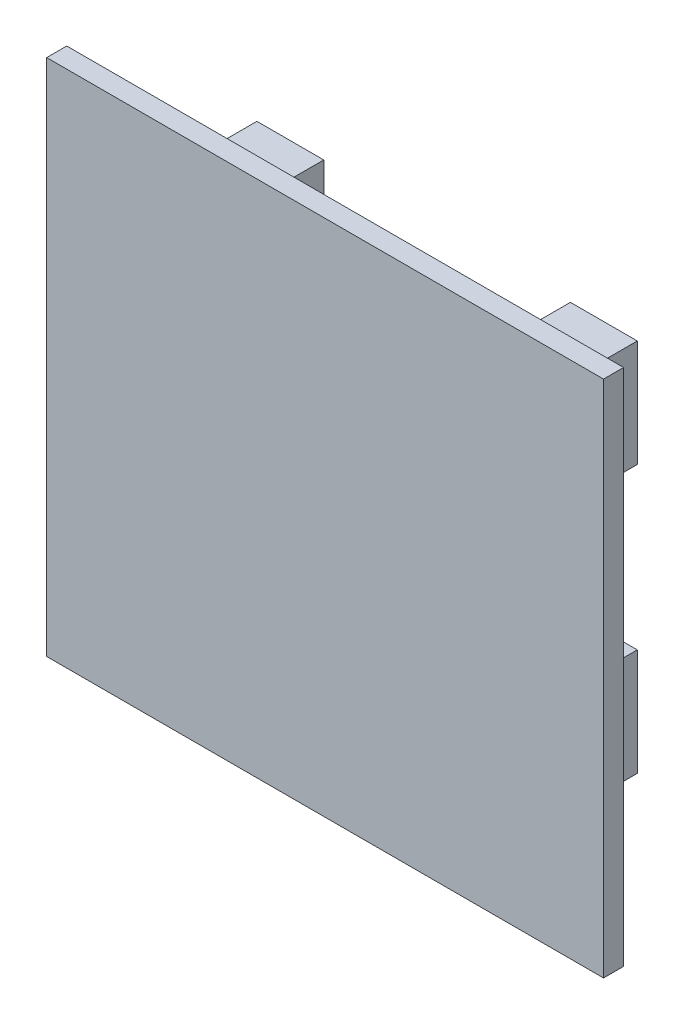
SolidWorks part; units mm, degrees
ref_plane "Front Plane" through (0, 0, 0) normal (0, 0, 1) x (1, 0, 0)
ref_plane "Top Plane" through (0, 0, 0) normal (0, 1, 0) x (1, 0, 0)
ref_plane "Right Plane" through (0, 0, 0) normal (1, 0, 0) x (0, 0, -1)
sketch "Sketch1" plane through (0, 0, 0) normal (0, 0, 1) x (1, 0, 0)
  line L1 (-208.15, 193.891) -> (208.15, 193.891)
  line L2 (-208.15, 193.891) -> (-208.15, -193.891)
  line L3 (-208.15, -193.891) -> (208.15, -193.891)
  line L4 (208.15, 193.891) -> (208.15, -193.891)
  line L5 (-208.15, 193.891) -> (208.15, -193.891) construction
  line L6 (-208.15, -193.891) -> (208.15, 193.891) construction
  point P0 (0, 0)
  dimension "D1" = 416.3
  dimension "D2" = 387.782
extrude "Boss-Extrude1" add sketch "Sketch1" along normal mid plane 15
sketch "Sketch3" plane through (0, 0, -7.5) normal (0, 0, -1) x (-1, 0, 0)
  line L0 (-300.2235, 0) -> (-180.2235, 0) construction
  line L1 (0, 239.7758) -> (0, -251.8653) construction
  line L3 (92.2, 140) -> (142.2, 140)
  line L4 (92.2, 140) -> (92.2, 60)
  line L5 (92.2, 60) -> (142.2, 60)
  line L6 (142.2, 140) -> (142.2, 60)
  line L7 (92.2, 140) -> (142.2, 60) construction
  line L8 (92.2, 60) -> (142.2, 140) construction
  line L9 (92.2, -60) -> (142.2, -140) construction
  line L10 (92.2, -140) -> (142.2, -60) construction
  line L11 (142.2, -140) -> (142.2, -60)
  line L12 (92.2, -60) -> (142.2, -60)
  line L13 (92.2, -140) -> (92.2, -60)
  line L14 (92.2, -140) -> (142.2, -140)
  line L15 (-92.2, -140) -> (-142.2, -60) construction
  line L16 (-92.2, -60) -> (-142.2, -140) construction
  line L17 (-92.2, 60) -> (-142.2, 140) construction
  line L18 (-92.2, 140) -> (-142.2, 60) construction
  line L19 (-92.2, -140) -> (-142.2, -140)
  line L20 (-92.2, -140) -> (-92.2, -60)
  line L21 (-92.2, -60) -> (-142.2, -60)
  line L22 (-142.2, -140) -> (-142.2, -60)
  line L23 (-142.2, 140) -> (-142.2, 60)
  line L24 (-92.2, 60) -> (-142.2, 60)
  line L25 (-92.2, 140) -> (-92.2, 60)
  line L26 (-92.2, 140) -> (-142.2, 140)
  line L27 (315.1093, 0) -> (-348.5322, 0) construction
  line L28 (-25, 40) -> (25, 40)
  line L29 (-25, 40) -> (-25, -40)
  line L30 (-25, -40) -> (25, -40)
  line L31 (25, 40) -> (25, -40)
  line L32 (-25, 40) -> (25, -40) construction
  line L33 (-25, -40) -> (25, 40) construction
  point P5 (117.2, 100)
  point P16 (117.2, -100)
  point P25 (-117.2, -100)
  point P26 (-117.2, 100)
  point P27 (0, 0)
  dimension "D1" = 80
  dimension "D2" = 100
  dimension "D3" = 50
  dimension "D4" = 100
  dimension "D5" = 80
  dimension "D6" = 50
extrude "Boss-Extrude2" add sketch "Sketch3" along normal blind 76.2
sketch "Sketch5" plane through (-142.2, 0, 0) normal (-1, 0, 0) x (0, 0, 1)
  line L0 (55.6499, 100) -> (-146.8499, 100) construction
  line L1 (-45.6, 187.9772) -> (-45.6, -258.3282) construction
  line L2 (-119.6484, -100) -> (118.1125, -100) construction
  line L7 (-83.7, 60) -> (-7.5, 60) construction
  line L8 (-83.7, -140) -> (-7.5, -140) construction
  line L9 (-83.7, 60) -> (-83.7, 140) construction
  circle A0 centre (-45.6, 100) radius 15.5
  circle A1 centre (-45.6, -100) radius 15.5
  dimension "D1" = 40
  dimension "D2" = 40
  dimension "D3" = 38.1
  dimension "D4" = 200
extrude "Cut-Extrude1" cut sketch "Sketch5" against normal through all
sketch "Sketch6" plane through (25, 0, 0) normal (1, 0, 0) x (0, 0, -1)
  line L0 (0, 0) -> (208.5683, 0) construction
  line L1 (45.6, 0) -> (45.6, 228.6937) construction
  line L2 (83.7, 40) -> (83.7, -40) construction
  line L4 (83.7, -40) -> (7.5, -40) construction
  line L5 (83.7, 40) -> (7.5, 40) construction
  circle A0 centre (45.6, 0) radius 15.5
  dimension "D1" = 31
  dimension "D2" = 38.1
  dimension "D3" = 40
  dimension "D4" = 40
extrude "Cut-Extrude2" cut sketch "Sketch6" against normal through all
